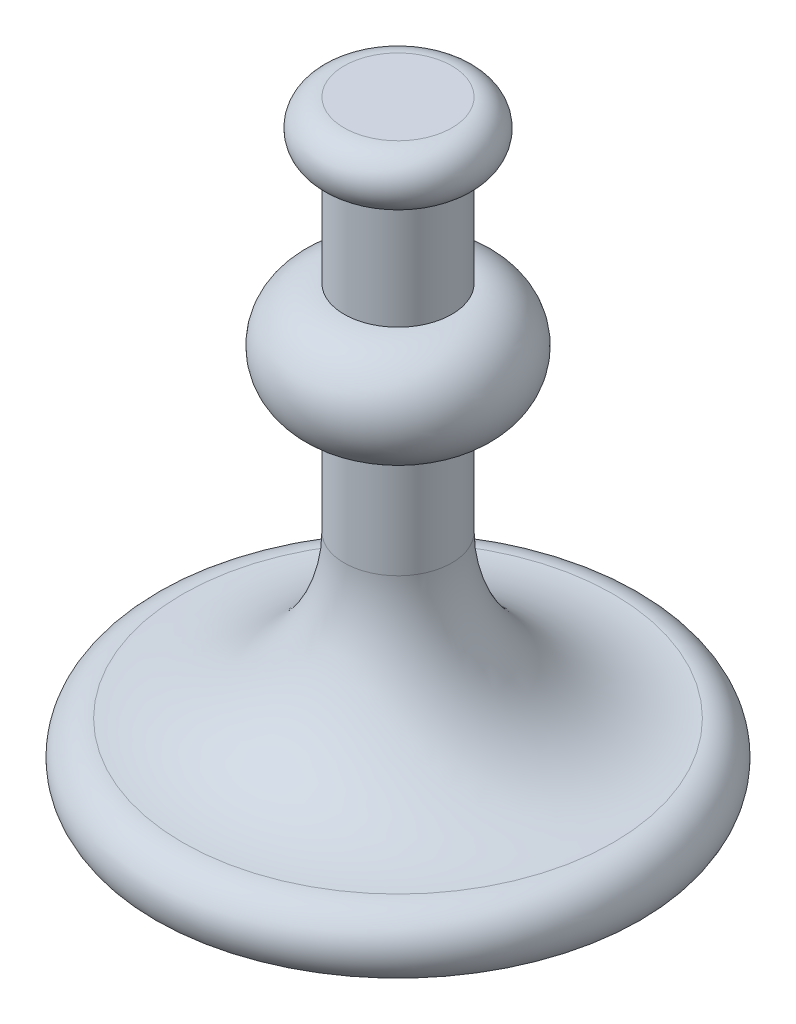
SolidWorks part; units mm, degrees
ref_plane "Front" through (0, 0, 0) normal (0, 0, 1) x (1, 0, 0)
ref_plane "Top" through (0, 0, 0) normal (0, 1, 0) x (1, 0, 0)
ref_plane "Right" through (0, 0, 0) normal (1, 0, 0) x (0, 0, -1)
sketch "Sketch1" plane through (0, 0, 0) normal (0, 0, 1) x (1, 0, 0)
  line L0 (0, 0) -> (0, 220)
  line L1 (0, 220) -> (20, 220)
  line L2 (0, 0) -> (90, 0)
  line L3 (20, 200) -> (20, 160)
  line L4 (20, 120) -> (20, 80)
  arc A0 (20, 220) -> (20, 200) centre (20, 210) cw
  arc A1 (20, 160) -> (20, 120) centre (20, 140) cw
  arc A2 (20, 80) -> (80, 20) centre (80, 80) ccw
  arc A3 (80, 20) -> (90, 0) centre (80, 7.5) cw
  dimension "D4" = 10
  dimension "D7" = 20
  dimension "D8" = 60
  dimension "D9" = 12.5
  dimension "D1" = 20
  dimension "D2" = 220
  dimension "D3" = 90
  dimension "D5" = 80
  dimension "D6" = 40
revolve "Revolve1" add sketch "Sketch1" angle 360 about L0
